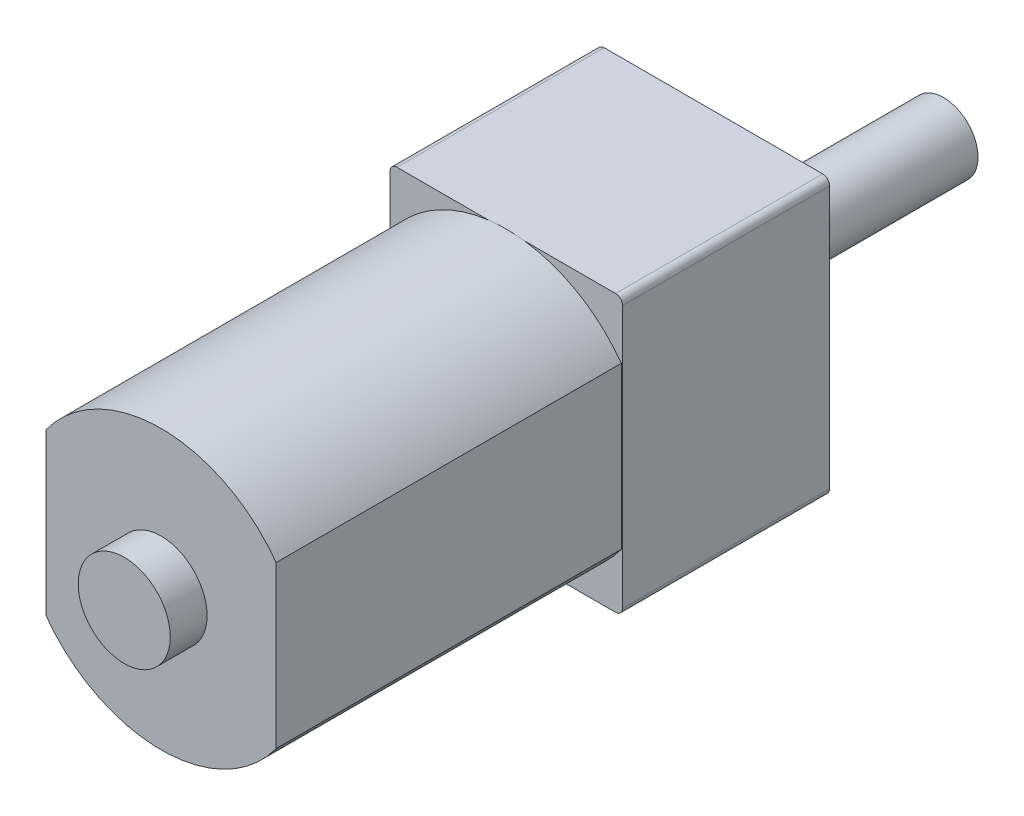
SolidWorks part; units mm, degrees
ref_plane "Plan de face" through (0, 0, 0) normal (0, 0, 1) x (1, 0, 0)
ref_plane "Plan de dessus" through (0, 0, 0) normal (0, 1, 0) x (1, 0, 0)
ref_plane "Plan de droite" through (0, 0, 0) normal (1, 0, 0) x (0, 0, -1)
sketch "Esquisse1" plane through (0, 0, 0) normal (0, 0, 1) x (1, 0, 0)
  line L0 (5, -3.5) -> (5, 3.5)
  line L1 (-5, -3.5) -> (-5, 3.5)
  line L2 (5, 0) -> (-5, 0) construction
  arc A0 (-5, 3.5) -> (5, 3.5) centre (0, -0.127) cw
  arc A1 (5, -3.5) -> (-5, -3.5) centre (0, 0.127) cw
  point P3 (5, 0)
  point P6 (-5, 0)
  point P10 (0, 0)
  point P13 (0, 6.05)
  point P14 (0, -6.05)
  dimension "D1" = 10
  dimension "D2" = 12.1
  dimension "D3" = 7
extrude "Boss.-Extru.1" add sketch "Esquisse1" along normal blind 15
sketch "Esquisse2" plane through (0, 0, 0) normal (0, 0, -1) x (-1, 0, 0)
  line L1 (5.05, -6) -> (-5.05, -6)
  line L2 (5.05, -6) -> (5.05, 6)
  line L3 (5.05, 6) -> (-5.05, 6)
  line L4 (-5.05, -6) -> (-5.05, 6)
  line L5 (5.05, -6) -> (-5.05, 6) construction
  line L6 (5.05, 6) -> (-5.05, -6) construction
  point P0 (0, 0)
  dimension "D1" = 12
  dimension "D2" = 10.1
extrude "Boss.-Extru.2" add sketch "Esquisse2" along normal blind 9
sketch "Esquisse3" plane through (0, 0, -9) normal (0, 0, -1) x (-1, 0, 0)
  line L0 (1, -1.118) -> (1, 1.118)
  arc A0 (1, 1.118) -> (1, -1.118) centre (0, 0) ccw
  point P1 (-1.5, 0)
  dimension "D1" = 3
  dimension "D2" = 2.5
extrude "Boss.-Extru.3" add sketch "Esquisse3" along normal blind 10
sketch "Esquisse4" plane through (0, 0, -9) normal (0, 0, -1) x (-1, 0, 0)
  circle A0 centre (0, 0) radius 2
  dimension "D1" = 4
extrude "Boss.-Extru.4" add sketch "Esquisse4" along normal blind 1
sketch "Esquisse5" plane through (0, 0, 15) normal (0, 0, 1) x (1, 0, 0)
  circle A0 centre (0, 0) radius 2
  dimension "D1" = 4
extrude "Boss.-Extru.5" add sketch "Esquisse5" along normal blind 1.6
fillet "Congé1" radius 0.3 4 edges at (5.05, -6, -4.5) (-5.05, -6, -4.5) (5.05, 6, -4.5) (-5.05, 6, -4.5)
